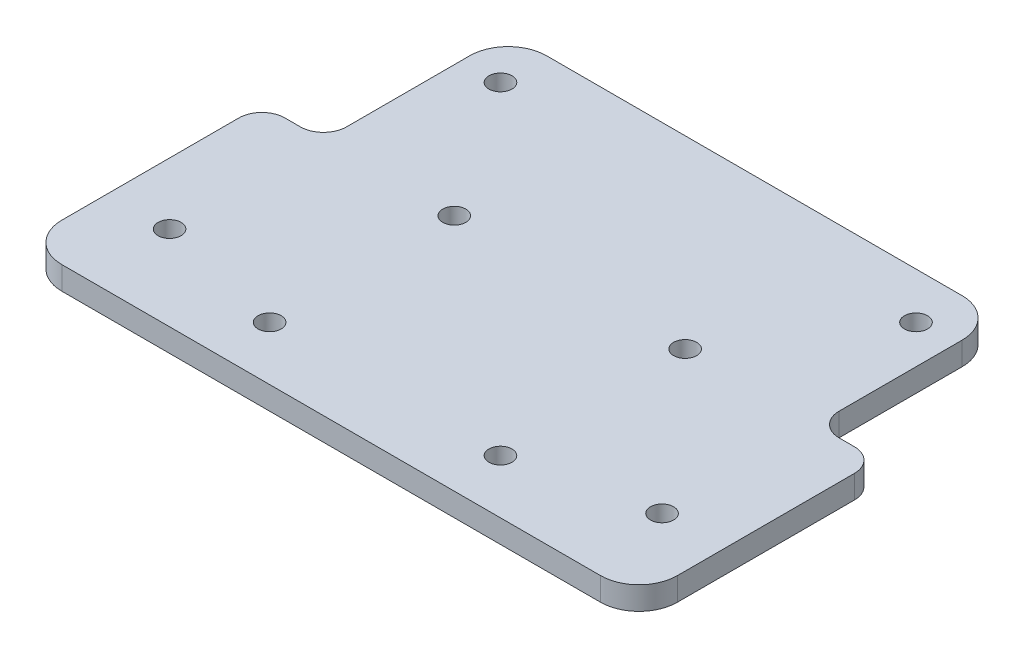
SolidWorks part; units mm, degrees
material "Thornel Mat VMA"
ref_plane "前视基准面" through (0, 0, 0) normal (0, 0, 1) x (1, 0, 0)
ref_plane "上视基准面" through (0, 0, 0) normal (0, 1, 0) x (1, 0, 0)
ref_plane "右视基准面" through (0, 0, 0) normal (1, 0, 0) x (0, 0, -1)
other "Configuration Table"
sketch "草图1" plane through (0, 0, 0) normal (0, 1, 0) x (1, 0, 0)
  line L1 (-40, -25) -> (40, -25)
  line L2 (-40, -25) -> (-40, 25)
  line L3 (-40, 25) -> (40, 25)
  line L4 (40, -25) -> (40, 25)
  line L5 (-40, -25) -> (40, 25) construction
  line L6 (-40, 25) -> (40, -25) construction
  line L7 (-32, 25) -> (-32, 1)
  line L8 (-32, 1) -> (-40, 1)
  line L9 (0, 0) -> (0, 25) construction
  line L10 (32, 1) -> (40, 1)
  line L11 (32, 25) -> (32, 1)
  point P0 (0, 0)
  dimension "D1" = 80
  dimension "D2" = 50
  dimension "D3" = 8
  dimension "D4" = 24
extrude "凸台-拉伸1" add sketch "草图1" along normal blind 3
sketch "草图2" plane through (0, 3, 0) normal (0, 1, 0) x (1, 0, 0)
  line L5 (0, 0) -> (0, 27.913) construction
  line L7 (0, 0) -> (-46.8963, 0) construction
  circle A1 centre (-32, -19) radius 1.5
  circle A2 centre (32, -19) radius 1.5
  circle A4 centre (-27, 19) radius 1.5
  circle A5 centre (27, 19) radius 1.5
  dimension "D1" = 3
  dimension "D2" = 3
  dimension "D3" = 27
  dimension "D4" = 19
  dimension "D5" = 32
  dimension "D6" = 19
extrude "切除-拉伸1" cut sketch "草图2" against normal blind 3
fillet "圆角1" radius 3 4 edges at (40, 1.5, -1) (32, 1.5, -1) (-40, 1.5, -1) (-32, 1.5, -1)
sketch "草图3" plane through (0, 3, 0) normal (0, 1, 0) x (1, 0, 0)
  line L0 (0, 0) -> (0, 28.9408) construction
  line L1 (0, 0) -> (46.1897, 0) construction
  line L2 (0, 0) -> (0, -30.0972) construction
  line L3 (0, -11) -> (23.6409, -11) construction
  circle A0 centre (-15, 1) radius 1.5
  circle A2 centre (-15, -23) radius 1.5
  circle A3 centre (15, -23) radius 1.5
  circle A4 centre (15, 1) radius 1.5
  dimension "D1" = 3
  dimension "D2" = 24
  dimension "D3" = 30
  dimension "D4" = 11
extrude "切除-拉伸2" cut sketch "草图3" against normal blind 10
sketch "草图4" plane through (0, 3, 0) normal (0, 1, 0) x (1, 0, 0)
  line L0 (-40, -25) -> (-40, -30)
  line L1 (-40, -30) -> (40, -30)
  line L2 (40, -30) -> (40, -25)
  line L3 (-40, -25) -> (40, -25) construction
  line L4 (40, -25) -> (-40, -25)
  dimension "D1" = 80
  dimension "D2" = 5
extrude "凸台-拉伸2" add sketch "草图4" against normal blind 3
fillet "圆角2" radius 5 4 edges at (-32, 1.5, -25) (32, 1.5, -25) (40, 1.5, 30) (-40, 1.5, 30)
